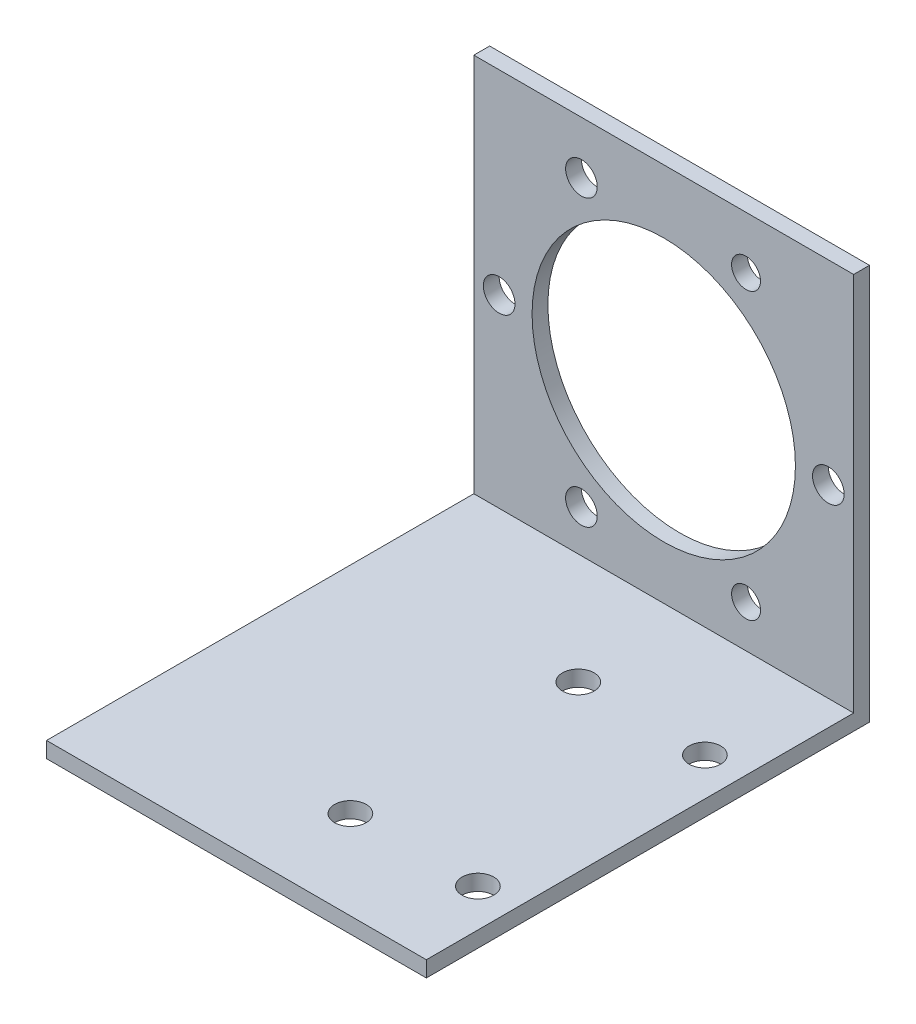
SolidWorks part; units mm, degrees
ref_plane "Front Plane" through (0, 0, 0) normal (0, 0, 1) x (1, 0, 0)
ref_plane "Top Plane" through (0, 0, 0) normal (0, 1, 0) x (1, 0, 0)
ref_plane "Right Plane" through (0, 0, 0) normal (1, 0, 0) x (0, 0, -1)
sketch "Sketch1" plane through (0, 0, 0) normal (0, 0, 1) x (1, 0, 0)
  line L1 (0, 0) -> (38.1, 0)
  line L2 (0, 0) -> (0, 1.5875)
  line L3 (0, 1.5875) -> (38.1, 1.5875)
  line L4 (38.1, 0) -> (38.1, 1.5875)
  dimension "D1" = 38.1
  dimension "D2" = 1.5875
extrude "Boss-Extrude1" add sketch "Sketch1" along normal blind 44.45
sketch "Sketch2" plane through (0, 1.5875, 0) normal (0, 1, 0) x (1, 0, 0)
  line L0 (21.59, -44.45) -> (21.59, 0) construction
  line L1 (38.1, -44.45) -> (0, -44.45) construction
  line L2 (38.1, 0) -> (0, 0) construction
  line L3 (34.29, 0) -> (34.29, -44.45) construction
  line L4 (38.1, -44.45) -> (38.1, 0) construction
  line L5 (0, 0) -> (38.1, 0)
  line L6 (0, 0) -> (0, -1.5875)
  line L7 (0, -1.5875) -> (38.1, -1.5875)
  line L8 (38.1, 0) -> (38.1, -1.5875)
  line L10 (0, -44.45) -> (0, 0) construction
  circle A0 centre (21.59, -12.7) radius 1.5875 construction
  circle A2 centre (21.59, -35.56) radius 1.5875 construction
  circle A3 centre (34.29, -35.4699) radius 1.5875 construction
  circle A5 centre (34.29, -12.7) radius 1.5875 construction
  point P10 (0, 0)
  dimension "D3" = 3.175
  dimension "D6" = 3.175
  dimension "D9" = 3.175
  dimension "D10" = 3.175
  dimension "D4" = 12.7
  dimension "D5" = 12.7
  dimension "D8" = 8.9801
  dimension "D11" = 8.89
  dimension "D12" = 1.5875
  dimension "D13" = 12.7
  dimension "D14" = 21.59
extrude "Boss-Extrude2" add sketch "Sketch2" along normal blind 38.1
sketch "Sketch3" plane through (0, 0, 0) normal (0, 0, -1) x (-1, 0, 0)
  line L0 (0, 0) -> (-38.1, 0) construction
  line L1 (-38.1, 20.1295) -> (0, 20.1295) construction
  line L2 (-38.1, 0) -> (-38.1, 39.6875) construction
  line L3 (0, 39.6875) -> (0, 0) construction
  line L4 (-19.05, 20.1295) -> (-11.3996, 33.3803) construction
  line L5 (-19.05, 20.1295) -> (-10.602, 5.4972) construction
  line L6 (-19.05, 20.1295) -> (-29.4645, 38.1679) construction
  line L7 (-19.05, 20.1295) -> (-30.7265, -0.0948) construction
  circle A0 centre (-19.05, 20.1295) radius 13.208
  point P6 (-10.795, 5.8314)
  point P11 (-19.05, 20.1295)
  point P14 (-2.54, 20.1295)
  point P15 (-10.795, 34.4276)
  point P16 (-35.56, 20.1295)
  point P17 (-27.305, 5.8314)
  point P20 (-27.305, 34.4276)
  dimension "D3" = 26.416
  dimension ".7" = 20.1295
  dimension "D2" = 19.05
  dimension "D4" = 60
  dimension "D5" = 60
  dimension "D6" = 16.51
  dimension "D7" = 16.51
  dimension "D8" = 16.51
  dimension "D9" = 16.51
  dimension "D10" = 60
  dimension "D11" = 60
  dimension "D12" = 16.51
  dimension "D13" = 16.51
extrude "Cut-Extrude1" cut sketch "Sketch3" against normal through all contours A0
hole_wizard "1/8 (0.125) Diameter Hole3" positions "Sketch13" profile "Sketch12" hole size "1/8" standard "ANSI Inch" end condition through all
sketch "Sketch13" plane through (0, 0, 0) normal (0, 0, -1) x (-1, 0, 0)
  point P0 (-35.56, 20.1295)
  point P3 (-10.795, 34.4276)
  point P6 (-2.54, 20.1295)
  point P9 (-10.795, 5.8314)
sketch "Sketch12" plane through (35.56, 20.1295, 0) normal (1, 0, 0) x (0, 1, 0)
  line L0 (0, 0) -> (0, 44.45)
  line L1 (0, 44.45) -> (1.5875, 44.45)
  line L2 (1.5875, 44.45) -> (1.5875, 0)
  line L5 (1.5875, 0) -> (0, 0)
  line L11 (0, -6.35) -> (0, 107.95) construction
  dimension "Thru Hole Dia." = 3.175
  dimension "Thru Hole Depth" = 44.45
hole_wizard "1/8 (0.125) Diameter Hole4" positions "Sketch14" profile "Sketch15" hole size "1/8" standard "ANSI Inch" end condition through all
sketch "Sketch14" plane through (0, 1.5875, 0) normal (0, 1, 0) x (1, 0, 0)
  point P0 (34.29, -12.7)
  point P3 (21.59, -12.7)
  point P6 (21.59, -35.56)
  point P9 (34.29, -35.4699)
sketch "Sketch15" plane through (34.29, 1.5875, 12.7) normal (1, 0, 0) x (0, 0, 1)
  line L0 (0, 0) -> (0, 1.5875)
  line L1 (0, 1.5875) -> (1.5875, 1.5875)
  line L2 (1.5875, 1.5875) -> (1.5875, 0)
  line L5 (1.5875, 0) -> (0, 0)
  line L11 (0, -6.35) -> (0, 107.95) construction
  dimension "Thru Hole Dia." = 3.175
  dimension "Thru Hole Depth" = 1.5875
hole_wizard "Ø2.9 (2.9) Diameter Hole1" positions "Sketch16" profile "Sketch17" hole size "Ø2.9" standard "ANSI Metric"
sketch "Sketch16" plane through (0, 0, 0) normal (0, 0, -1) x (-1, 0, 0)
  point P0 (-27.305, 5.8314)
  point P3 (-27.305, 34.4276)
sketch "Sketch17" plane through (27.305, 5.8314, 0) normal (1, 0, 0) x (0, 1, 0)
  line L0 (0, 0) -> (0, 4.4272)
  line L1 (0, 4.4272) -> (1.45, 3.556)
  line L2 (1.45, 3.556) -> (1.45, 0)
  line L5 (1.45, 0) -> (0, 0)
  line L10 (0, 4.4272) -> (-1.45, 3.556) construction
  line L11 (0, -6.35) -> (0, 107.95) construction
  dimension "Hole Dia." = 2.9
  dimension "Hole Depth" = 3.556
  dimension "Drill Angle" = 118
